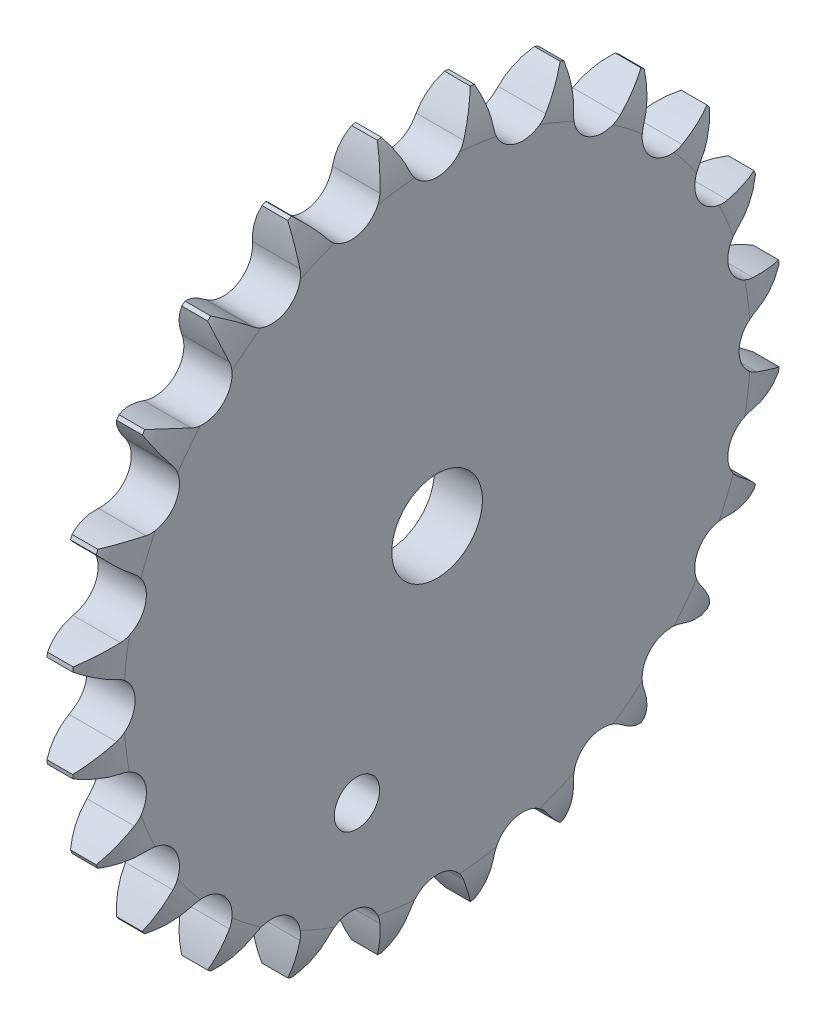
SolidWorks part; units mm, degrees
ref_plane "Plane1" through (0, 0, 0) normal (0, 0, 1) x (1, 0, 0)
ref_plane "Plane2" through (0, 0, 0) normal (0, 1, 0) x (1, 0, 0)
ref_plane "Plane3" through (0, 0, 0) normal (1, 0, 0) x (0, 0, -1)
sketch "Clipboard" plane through (0, 0, 0) normal (0, 1, 0) x (1, 0, 0)
  line L0 (0, 0) -> (8.7015, -3.8742)
  line L1 (-15, 0) -> (100, 0) construction
  line L2 (0, 0) -> (-0.8203, 0.9272)
  line L3 (0, 0) -> (-8.8973, 3.4006)
  line L4 (0, 0) -> (2.832, 1.2609)
  line L5 (0, 0) -> (-46.8476, -17.4728)
  line L6 (0, 0) -> (-4.4098, -2.9753)
  line L7 (-0.8203, 0.9272) -> (44.4955, 22.0583)
  line L8 (-76.2, 38.1) -> (-74.4, 38.1)
  line L9 (-73.3242, 40.7328) -> (-72.926, 40.7699)
  line L10 (-73.4529, 9.1872) -> (-63.2129, 9.1872)
  circle A0 centre (0, 0) radius 3.175
  circle A1 centre (0, 0) radius 31.4996
  circle A2 centre (0, 0) radius 37.5
  dimension "Dr" = 6.35
  dimension "MHD" = 62.9992
  dimension "Hub_dia" = 75
  dimension "Num_teeth" = 24
  dimension "Pitch" = 9.525
  dimension "Width" = 3.1
  dimension "Side_relief" = 1.238
  dimension "Side_radius" = 9.525
  dimension "Overall_len" = 50
  dimension "Show_teeth" = 24
  dimension "Thickness" = 5.3196
  dimension "OAL" = 50.0005
  dimension "T_dim" = 1.8
  dimension "Fillet_rad" = 0.4
  dimension "Face_width" = 5.32
  dimension "Num_strands" = 1
  dimension "Transv_pitch" = 10.24
  dimension "Plate_wid" = 8.26
sketch "BasProSke" plane through (0, 0, 0) normal (0, 1, 0) x (1, 0, 0)
  line L0 (-10, 0) -> (60, 0) construction
  line L1 (0, 0) -> (0, 34.5692)
  line L2 (0, 0) -> (5.3196, 0)
  line L3 (5.3196, 0) -> (5.3196, 34.5692)
  line L4 (4.0816, 39.2651) -> (1.238, 39.2651)
  arc A0 (0, 34.5692) -> (1.238, 39.2651) centre (9.525, 34.5692) cw
  arc A1 (5.3196, 34.5692) -> (4.0816, 39.2651) centre (-4.2054, 34.5692) ccw
  dimension "Thickness" = 5.3196
  dimension "D1" = 9.525
  dimension "G1" = 1.238
  dimension "G2" = 1.238
  dimension "Diameter" = 78.5301
revolve "Base-Revolve" add sketch "BasProSke" angle 360 about L0
sketch "TooCutSke" plane through (0, 0, 0) normal (1, 0, 0) x (0, 0, -1)
  line L0 (0, 36.5187) -> (2.9759, 35.3239) construction
  line L1 (0, 0) -> (0, 107) construction
  line L2 (0, 36.5187) -> (-10, 36.5187) construction
  line L3 (0, 36.5187) -> (-2.9759, 35.3239) construction
  arc A0 (2.9759, 35.3239) -> (5.214, 39.4217) centre (21.3614, 27.9423) cw
  arc A1 (2.9759, 35.3239) -> (-2.9759, 35.3239) centre (0, 36.5187) cw
  arc A2 (-2.9759, 35.3239) -> (-5.214, 39.4217) centre (-21.3614, 27.9423) ccw
  arc A3 (5.214, 39.4217) -> (-5.214, 39.4217) centre (0, 0) ccw
  dimension "R1" = 3.2067
  dimension "R2" = 19.812
  dimension "Overcut" = 39.7651
  dimension "Seat_radius" = 36.5187
  dimension "X" = 136.25
extrude "ToothCut" cut sketch "TooCutSke" along normal through all
pattern_circular "TeethCuts" count 24 every 15 about axis through (-10, 0, 0) along (1, 0, 0) of "ToothCut"
sketch "HubNeaOneSke" plane through (0, 0, 0) normal (-1, 0, 0) x (0, 0, 1)
  circle A0 centre (0, 0) radius 31.4996
  dimension "Diameter" = 62.9992
extrude "HubNearOne" [suppressed] add sketch "HubNeaOneSke" along normal blind 44.6809
fillet "HubNearOneFillet" [suppressed] radius 0.4
sketch "HubNeaBotSke" plane through (0, 0, 0) normal (-1, 0, 0) x (0, 0, 1)
  circle A0 centre (0, 0) radius 31.4996
  dimension "Diameter" = 62.9992
extrude "HubNearBoth" [suppressed] add sketch "HubNeaBotSke" along normal blind 22.3405
fillet "HubNearBothFillet" [suppressed] radius 0.4
ref_plane "FarPln" through (5.3196, 0, 0) normal (1, 0, 0) x (0, 0, -1)
sketch "HubFarSke" plane through (5.3196, 0, 0) normal (1, 0, 0) x (0, 0, -1)
  circle A0 centre (0, 0) radius 31.4996
  dimension "Diameter" = 62.9992
extrude "HubFar" [suppressed] add sketch "HubFarSke" along normal blind 22.3405
fillet "HubFarFillet" [suppressed] radius 0.4
sketch "BorSke" plane through (0, 0, 0) normal (1, 0, 0) x (0, 0, -1)
  circle A0 centre (0, 0) radius 5
  dimension "Diameter" = 10
extrude "Bore" cut sketch "BorSke" along normal mid plane 100.001
sketch "KeySke" plane through (0, 0, 0) normal (1, 0, 0) x (0, 0, -1)
  line L0 (-2, 0) -> (-2, 6.8)
  line L1 (-2, 6.8) -> (2, 6.8)
  line L2 (2, 6.8) -> (2, 0)
  line L3 (0, 0) -> (0, 34) construction
  line L4 (-2, 0) -> (2, 0)
  dimension "Offset" = 6.8
  dimension "Width" = 4
extrude "Keyway" [suppressed] cut sketch "KeySke" along normal mid plane 100.001
pattern_circular "Keyway2" [suppressed] count 2 every 90 about axis through (-10, 0, 0) along (1, 0, 0)
hole_wizard "M6 Tapped Hole1" positions "Sketch3" profile "Sketch2" tap size "M6" standard "ISO"
sketch "Sketch3" plane through (5.3196, 0, 0) normal (1, 0, 0) x (0, 0, -1)
  point P0 (-8.8425, -22.0425)
  dimension "D1" = 23.75
sketch "Sketch2" plane through (5.3196, -22.0425, 8.8425) normal (0, 1, 0) x (0, 0, -1)
  line L0 (0, 0) -> (0, 16.5022)
  line L1 (0, 16.5022) -> (2.5, 15)
  line L2 (2.5, 15) -> (2.5, 0)
  line L5 (2.5, 0) -> (0, 0)
  line L10 (0, 16.5022) -> (-2.5, 15) construction
  line L11 (0, -6.35) -> (0, 107.95) construction
  dimension "Tap Drill Dia." = 5
  dimension "Tap Drill Depth" = 15
  dimension "Drill Angle" = 118
cosmetic thread "Hole Thread1" parameters "D1"=5.3196, "D2"=6
equation "' \"Pitch@Clipboard\" = 12.7"
equation "' \"Num_strands@Clipboard\" = 1"
equation "' \"Num_teeth@Clipboard\" = 9"
equation "' \"Hub_dia@Clipboard\" = 50"
equation "' \"Overall_len@Clipboard\" = 3"
equation "' \"Diameter@BorSke\" = 12"
equation "' \"T_dim@Clipboard\" = 1"
equation "' \"Width@KeySke\" = 2"
equation "' \"Dr@Clipboard\" = 8.51"
equation "' \"Face_width@Clipboard\" = 7.2"
equation "' \"Side_radius@Clipboard\" = 12.7"
equation "' \"Side_relief@Clipboard\" = 1.27"
equation "' \"Transv_pitch@Clipboard\" = 13.92"
equation "' \"Show_teeth@Clipboard\" = 9"
equation "' \"Fillet_rad@Clipboard\" = 0.6"
equation "' \"Plate_wid@Clipboard\" = 11.8"
equation "\"Num_teeth@Clipboard\" = int( \"Num_teeth@Clipboard\" )"
equation "\"Num_teeth@Clipboard\" = ((sgn( \"Num_teeth@Clipboard\" - 5.0)+1)*( \"Num_teeth@Clipboard\" - 5.0))/2 +5.0"
equation "\"Num_teeth@Clipboard\" = ((sgn( \"Num_teeth@Clipboard\" - 200.0)-1)*( \"Num_teeth@Clipboard\" - 200.0))/-2 +200.0"
equation "\"MHD@Clipboard\" = \"Pitch@Clipboard\" * (1.0 / tan(3.14159265 / \"Num_teeth@Clipboard\" )) - 1.04 * \"Plate_wid@Clipboard\" - 0.76"
equation "\"Thickness@Clipboard\"  = \"Face_width@Clipboard\" + (\"Num_strands@Clipboard\" - 1) * \"Transv_pitch@Clipboard\""
equation "\"OAL@Clipboard\" = \"Thickness@Clipboard\" + 2 * \"Fillet_rad@Clipboard\" + 1"
equation "\"MHD@Clipboard\" = ((sgn( \"MHD@Clipboard\" - \"Hub_dia@Clipboard\" )-1)*( \"MHD@Clipboard\" - \"Hub_dia@Clipboard\" ))/-2+ \"Hub_dia@Clipboard\""
equation "\"OAL@Clipboard\" = ((sgn( \"OAL@Clipboard\" - \"Overall_len@Clipboard\" )+1)*( \"OAL@Clipboard\" - \"Overall_len@Clipboard\" ))/2 + \"Overall_len@Clipboard\" + 0.0005"
equation "\"Num_teeth@TeethCuts\" = int( \"Show_teeth@Clipboard\" ) + 1"
equation "\"Num_teeth@TeethCuts\" = ((sgn( \"Num_teeth@TeethCuts\" - \"Num_teeth@Clipboard\" )-1)*( \"Num_teeth@TeethCuts\" - \"Num_teeth@Clipboard\" ))/-2+ \"Num_teeth@Clipboard\""
equation "\"Num_teeth@TeethCuts\" = ((sgn( \"Num_teeth@TeethCuts\" - 2.0)+1)*( \"Num_teeth@TeethCuts\" - 2.0))/2 +2.0"
equation "\"Angle@TeethCuts\" = 360.0 / \"Num_teeth@Clipboard\""
equation "\"Seat_radius@TooCutSke\" = ( \"Pitch@Clipboard\" / 2.0) / sin(3.14159265 / \"Num_teeth@Clipboard\" ) - \"Dr@Clipboard\" / 2.0 + \"Dr@Clipboard\" * 0.505"
equation "\"R1@TooCutSke\"  = \"Dr@Clipboard\" * 0.505"
equation "\"X@TooCutSke\" = 140.0 - (90.0 / \"Num_teeth@Clipboard\")"
equation "\"R2@TooCutSke\" = 0.12 * \"Dr@Clipboard\" * ( \"Num_teeth@Clipboard\" + 2.0)"
equation "\"Overcut@TooCutSke\" = 0.5 + 0.625 * \"Pitch@Clipboard\" - 0.5 * \"Dr@Clipboard\"  +  \"Pitch@Clipboard\" / 2.0 / sin(3.14159265 / \"Num_teeth@Clipboard\" )"
equation "\"Diameter@BasProSke\" = 2.0 * ( 0.625 * \"Pitch@Clipboard\" - 0.5 * \"Dr@Clipboard\"  +  \"Pitch@Clipboard\" / 2.0 / sin(3.14159265 / \"Num_teeth@Clipboard\" ))"
equation "\"Thickness@BasProSke\"  = \"Thickness@Clipboard\""
equation "\"G1@BasProSke\" =  \"Side_relief@Clipboard\""
equation "\"G2@BasProSke\" =  \"Side_relief@Clipboard\""
equation "\"D1@BasProSke\" =  \"Side_radius@Clipboard\""
equation "\"Diameter@HubNeaOneSke\" = \"MHD@Clipboard\""
equation "\"Length@HubNearOne\" = \"OAL@Clipboard\" - \"Thickness@BasProSke\""
equation "\"Diameter@HubNeaBotSke\" = \"MHD@Clipboard\""
equation "\"Length@HubNearBoth\" = ( \"OAL@Clipboard\" - \"Thickness@BasProSke\" ) / 2.0"
equation "\"D1@HubNearOneFillet\" = \"Fillet_rad@Clipboard\""
equation "\"D1@HubNearBothFillet\" = \"Fillet_rad@Clipboard\""
equation "\"Thickness@FarPln\" = \"Thickness@BasProSke\""
equation "\"Diameter@HubFarSke\" = \"MHD@Clipboard\""
equation "\"Length@HubFar\" = ( \"OAL@Clipboard\" - \"Thickness@BasProSke\" ) / 2.0"
equation "\"D1@HubFarFillet\" = \"Fillet_rad@Clipboard\""
equation "\"D1@Bore\" = \"OAL@Clipboard\" * 2.0"
equation "\"D1@Keyway\" = \"OAL@Clipboard\" * 2.0"
equation "\"Offset@KeySke\" = \"T_dim@Clipboard\" + \"Diameter@BorSke\" / 2.0"
